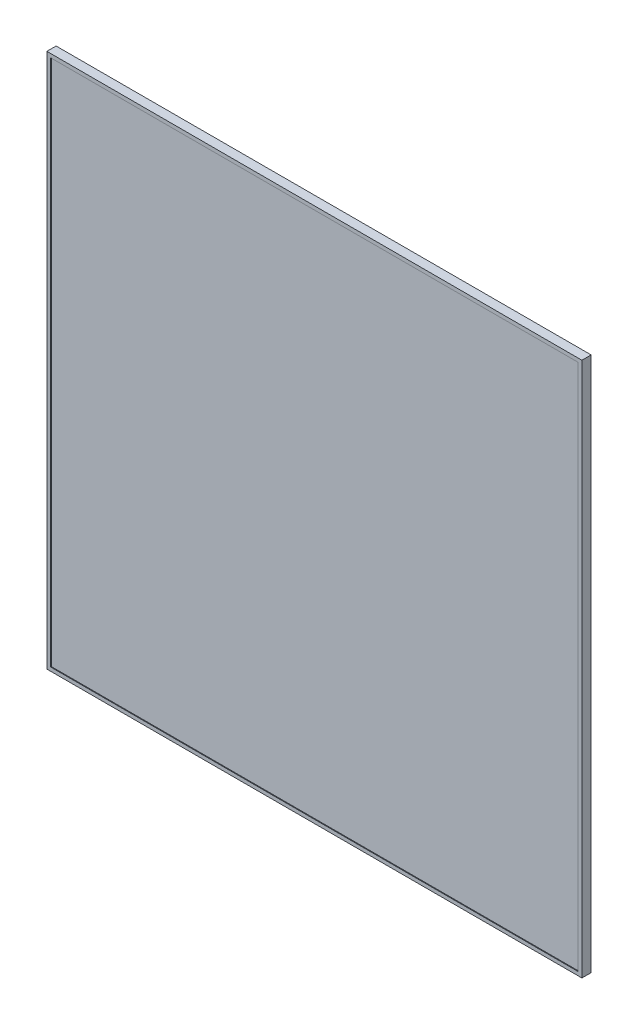
SolidWorks part; units mm, degrees
ref_plane "Plan de face" through (0, 0, 0) normal (0, 0, 1) x (1, 0, 0)
ref_plane "Plan de dessus" through (0, 0, 0) normal (0, 1, 0) x (1, 0, 0)
ref_plane "Plan de droite" through (0, 0, 0) normal (1, 0, 0) x (0, 0, -1)
sketch "Sketch1" plane through (0, 0, 0) normal (0, 0, 1) x (1, 0, 0)
  line L1 (-72.5, 72.5) -> (72.5, 72.5)
  line L2 (-72.5, 72.5) -> (-72.5, -72.5)
  line L3 (-72.5, -72.5) -> (72.5, -72.5)
  line L4 (72.5, 72.5) -> (72.5, -72.5)
  line L5 (-72.5, 72.5) -> (72.5, -72.5) construction
  line L6 (-72.5, -72.5) -> (72.5, 72.5) construction
  point P0 (0, 0)
  dimension "D1" = 145
  dimension "D2" = 145
extrude "Boss-Extrude1" add sketch "Sketch1" along normal mid plane 2.5
sketch "Sketch2" plane through (0, 0, 1.25) normal (0, 0, 1) x (1, 0, 0)
  line L0 (72.5, 72.5) -> (-72.5, 72.5) construction
  line L1 (71.5, -71.5) -> (-71.5, -71.5)
  line L2 (71.5, -71.5) -> (71.5, 71.5)
  line L3 (71.5, 71.5) -> (-71.5, 71.5)
  line L4 (-71.5, -71.5) -> (-71.5, 71.5)
  line L5 (71.5, -71.5) -> (-71.5, 71.5) construction
  line L6 (71.5, 71.5) -> (-71.5, -71.5) construction
  point P0 (0, 0)
  dimension "D1" = 1
extrude "Cut-Extrude1" cut sketch "Sketch2" against normal blind 0.2
